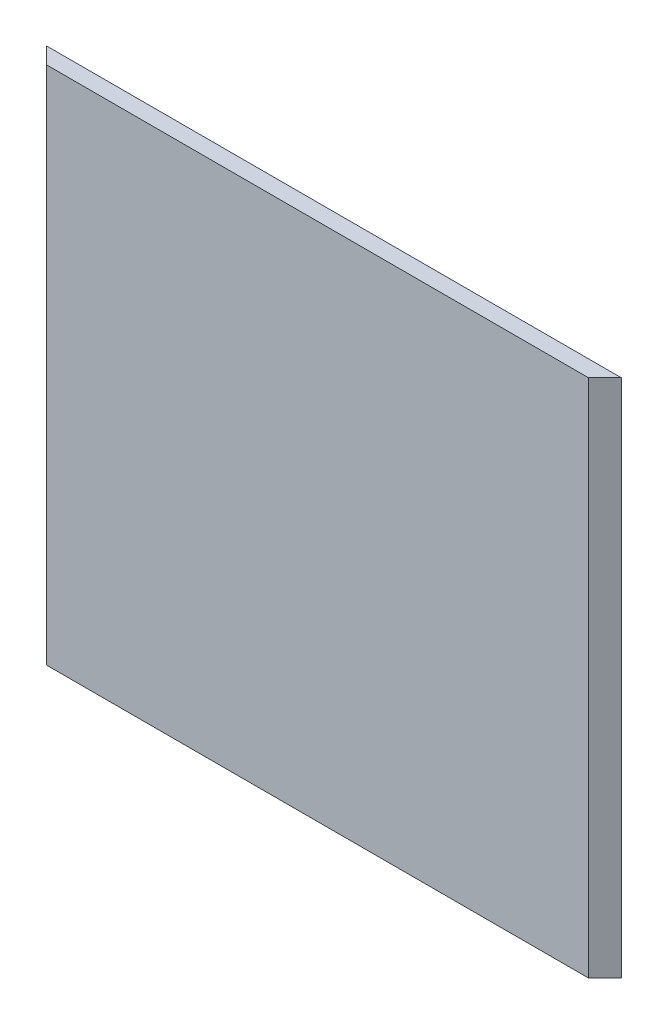
SolidWorks part; units mm, degrees
ref_plane "Front Plane" through (0, 0, 0) normal (0, 0, 1) x (1, 0, 0)
ref_plane "Top Plane" through (0, 0, 0) normal (0, 1, 0) x (1, 0, 0)
ref_plane "Right Plane" through (0, 0, 0) normal (1, 0, 0) x (0, 0, -1)
sketch "Sketch1" plane through (0, 0, 0) normal (0, 1, 0) x (1, 0, 0)
  line L0 (-52.5, 1.5) -> (-52.5, -1.5)
  line L1 (52.5, -1.5) -> (-52.5, -1.5)
  line L2 (52.5, -1.5) -> (52.5, 1.5)
  line L3 (52.5, 1.5) -> (-52.5, 1.5)
  line L4 (-52.5, -1.5) -> (-52.5, 1.5)
  line L5 (52.5, -1.5) -> (-52.5, 1.5) construction
  line L6 (52.5, 1.5) -> (-52.5, -1.5) construction
  line L7 (-49.5, -1.5) -> (-52.5, 1.5)
  line L8 (52.5, 1.5) -> (52.5, -1.5)
  line L9 (49.5, -1.5) -> (52.5, 1.5)
  point P0 (0, 0)
  dimension "D1" = 3
  dimension "D2" = 105
  dimension "D3" = 45
  dimension "D4" = 45
extrude "Boss-Extrude1" add sketch "Sketch1" along normal blind 95 contours L1 L9 L3 L7
